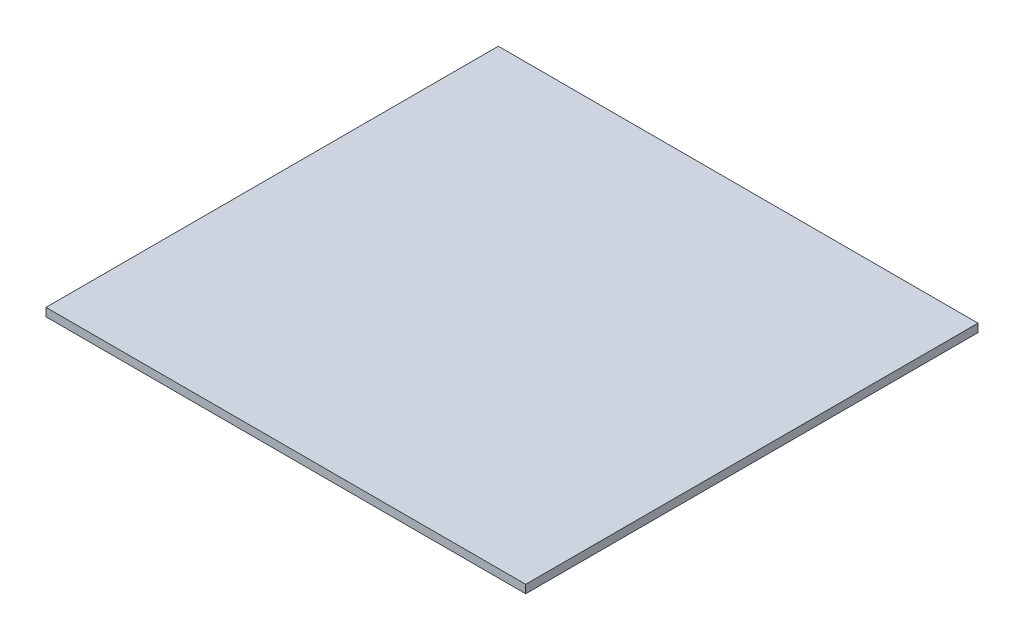
SolidWorks part; units mm, degrees
ref_plane "Plan de face" through (0, 0, 0) normal (0, 0, 1) x (1, 0, 0)
ref_plane "Plan de dessus" through (0, 0, 0) normal (0, 1, 0) x (1, 0, 0)
ref_plane "Plan de droite" through (0, 0, 0) normal (1, 0, 0) x (0, 0, -1)
sketch "Esquisse1" plane through (0, 0, 0) normal (0, 1, 0) x (1, 0, 0)
  line L1 (0, 0) -> (-350, 0)
  line L2 (0, 0) -> (0, 330)
  line L3 (0, 330) -> (-350, 330)
  line L4 (-350, 0) -> (-350, 330)
  dimension "D1" = 330
  dimension "D2" = 350
extrude "Boss.-Extru.1" add sketch "Esquisse1" along normal blind 6
